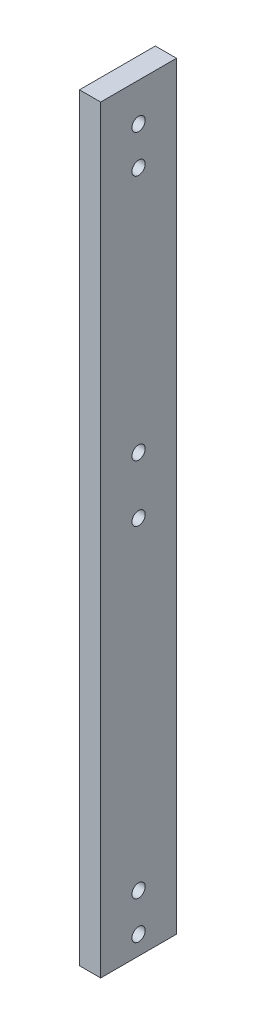
SolidWorks part; units mm, degrees
ref_plane "Front Plane" through (0, 0, 0) normal (0, 0, 1) x (1, 0, 0)
ref_plane "Top Plane" through (0, 0, 0) normal (0, 1, 0) x (1, 0, 0)
ref_plane "Right Plane" through (0, 0, 0) normal (1, 0, 0) x (0, 0, -1)
sketch "Sketch1" plane through (0, 0, 0) normal (1, 0, 0) x (0, 0, -1)
  line L1 (-6.7424, -63.9338) -> (13.2576, -63.9338)
  line L2 (-6.7424, -63.9338) -> (-6.7424, 136.0662)
  line L3 (-6.7424, 136.0662) -> (13.2576, 136.0662)
  line L4 (13.2576, -63.9338) -> (13.2576, 136.0662)
  dimension "D1" = 20
  dimension "D2" = 200
extrude "Boss-Extrude1" add sketch "Sketch1" along normal blind 5.588
sketch "Sketch2" plane through (5.588, 0, 0) normal (1, 0, 0) x (0, 0, -1)
  line L0 (3.2576, -63.9338) -> (3.2576, 136.0662) construction
  line L1 (-6.7424, -63.9338) -> (13.2576, -63.9338) construction
  line L2 (13.2576, 136.0662) -> (-6.7424, 136.0662) construction
  circle A0 centre (3.2576, -58.9338) radius 1.75
  circle A1 centre (3.2576, -48.9338) radius 1.75
  circle A2 centre (3.2576, 116.0662) radius 1.75
  circle A3 centre (3.2576, 126.0662) radius 1.75
  dimension "D1" = 3.5
  dimension "D2" = 10
  dimension "D3" = 10
  dimension "D4" = 10
  dimension "D5" = 5
extrude "Cut-Extrude1" cut sketch "Sketch2" against normal through all
sketch "Sketch3" plane through (5.588, 0, 0) normal (1, 0, 0) x (0, 0, -1)
  line L1 (3.2576, 36.0662) -> (3.2576, 51.0662) construction
  line L2 (3.2576, 51.0662) -> (3.2576, 136.0662) construction
  line L3 (13.2576, 136.0662) -> (-6.7424, 136.0662) construction
  line L4 (-6.7424, -63.9338) -> (13.2576, -63.9338) construction
  circle A0 centre (3.2576, 36.0662) radius 1.75
  circle A1 centre (3.2576, 51.0662) radius 1.75
  dimension "D1" = 3.5
  dimension "D2" = 15
  dimension "D3" = 100
extrude "Cut-Extrude2" cut sketch "Sketch3" against normal through all
